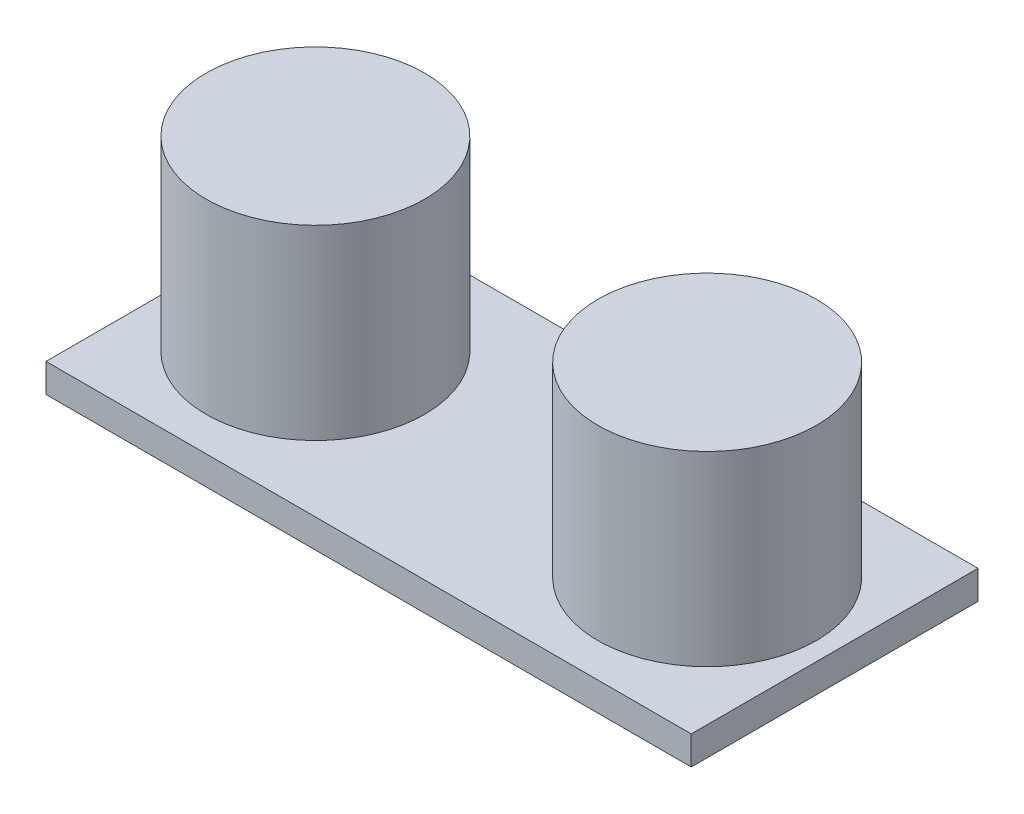
SolidWorks part; units mm, degrees
ref_plane "Front Plane" through (0, 0, 0) normal (0, 0, 1) x (1, 0, 0)
ref_plane "Top Plane" through (0, 0, 0) normal (0, 1, 0) x (1, 0, 0)
ref_plane "Right Plane" through (0, 0, 0) normal (1, 0, 0) x (0, 0, -1)
sketch "Sketch1" plane through (0, 0, 0) normal (0, 1, 0) x (1, 0, 0)
  line L1 (0, 0) -> (45, 0)
  line L2 (0, 0) -> (0, 20)
  line L3 (0, 20) -> (45, 20)
  line L4 (45, 0) -> (45, 20)
  dimension "D1" = 45
  dimension "D2" = 20
extrude "Boss-Extrude1" add sketch "Sketch1" along normal blind 2
sketch "Sketch2" plane through (0, 2, 0) normal (0, 1, 0) x (1, 0, 0)
  line L0 (45, 20) -> (0, 20) construction
  circle A0 centre (8.7875, 10) radius 7.62
  circle A1 centre (36.11, 10) radius 7.62
  dimension "D1" = 15.24
  dimension "D4" = 15.24
  dimension "D2" = 10
  dimension "D3" = 8.7875
  dimension "D5" = 10
  dimension "D6" = 8.89
extrude "Boss-Extrude2" add sketch "Sketch2" along normal blind 13
